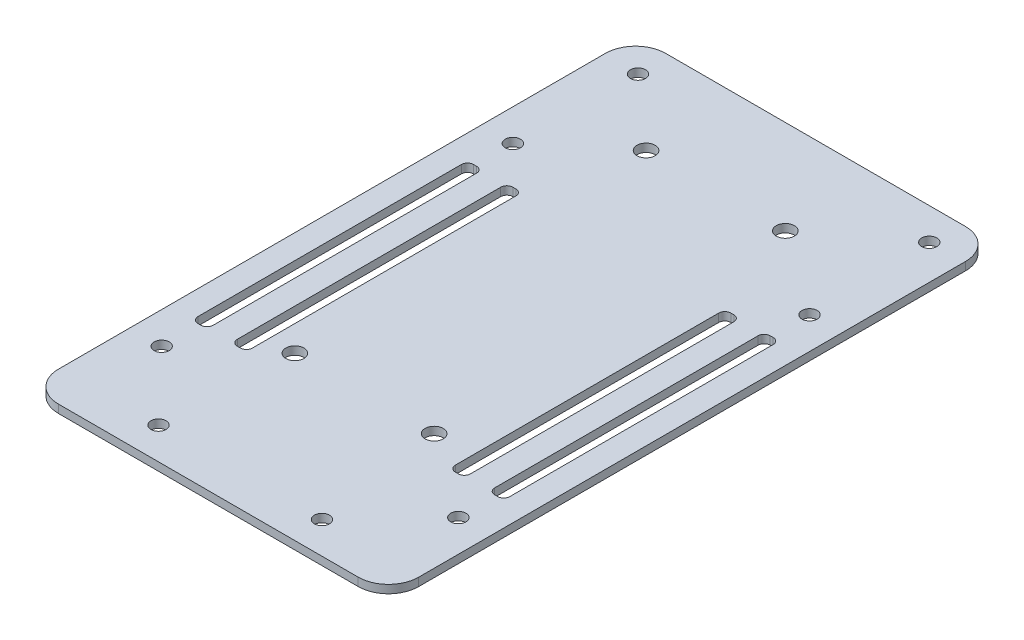
SolidWorks part; units mm, degrees
ref_plane "Front Plane" through (0, 0, 0) normal (0, 0, 1) x (1, 0, 0)
ref_plane "Top Plane" through (0, 0, 0) normal (0, 1, 0) x (1, 0, 0)
ref_plane "Right Plane" through (0, 0, 0) normal (1, 0, 0) x (0, 0, -1)
sketch "Sketch1" plane through (0, 0, 0) normal (0, 1, 0) x (1, 0, 0)
  line L0 (-14, 37.2419) -> (-14, -15.5619) construction
  line L1 (-14, 37.2419) -> (-14, -15.5619)
  line L2 (12, -15.5619) -> (12, 37.2419) construction
  line L3 (12, -15.5619) -> (12, 37.2419)
  line L4 (11, 43.34) -> (-13, 43.34)
  line L5 (-16, 40.34) -> (-16, -18.66)
  line L6 (-19.25, -26.0566) -> (-11.2385, -34.45)
  line L7 (-11.2385, -34.45) -> (11.2499, -34.45)
  line L8 (11.2499, -34.45) -> (19.25, -26.0457)
  line L9 (19.25, -26.0457) -> (19.25, 44.85)
  line L10 (19.25, 44.85) -> (-19.25, 44.85)
  line L11 (-19.25, 44.85) -> (-19.25, -26.0566)
  line L12 (-19.25, -26.0566) -> (-11.2385, -34.45)
  line L13 (-11.2385, -34.45) -> (11.2499, -34.45)
  line L14 (11.2499, -34.45) -> (19.25, -26.0457)
  line L15 (19.25, -26.0457) -> (19.25, 44.85)
  line L16 (19.25, 44.85) -> (-19.25, 44.85)
  line L17 (-19.25, 44.85) -> (-19.25, -26.0566)
  line L18 (-29.75, -30.2634) -> (-15.7315, -44.95)
  line L19 (-15.7315, -44.95) -> (15.7516, -44.95)
  line L20 (15.7516, -44.95) -> (29.75, -30.2443)
  line L21 (29.75, -30.2443) -> (29.75, 55.35)
  line L22 (29.75, 55.35) -> (-29.75, 55.35)
  line L23 (-29.75, 55.35) -> (-29.75, -30.2634)
  line L24 (-29.75, -30.2634) -> (-15.7315, -44.95)
  line L25 (-15.7315, -44.95) -> (15.7516, -44.95)
  line L26 (15.7516, -44.95) -> (29.75, -30.2443)
  line L27 (29.75, -30.2443) -> (29.75, 55.35)
  line L28 (29.75, 55.35) -> (-29.75, 55.35)
  line L29 (-29.75, 55.35) -> (-29.75, -30.2634)
  line L30 (-13, -21.66) -> (11, -21.66)
  line L31 (14, -18.66) -> (14, 40.34)
  line L32 (11, 43.34) -> (-13, 43.34)
  line L33 (-16, 40.34) -> (-16, -18.66)
  line L34 (-13, -21.66) -> (11, -21.66)
  line L35 (14, -18.66) -> (14, 40.34)
  line L36 (-9.9019, 41.34) -> (7.9019, 41.34) construction
  line L37 (-9.9019, 41.34) -> (7.9019, 41.34)
  line L38 (7.9029, -19.6617) -> (-9.9029, -19.6617) construction
  line L39 (7.9029, -19.6617) -> (-9.9029, -19.6617)
  circle A0 centre (10.5, -18.16) radius 1.5 construction
  circle A1 centre (-24.085, 50.1) radius 1.25
  circle A2 centre (-24.085, 50.1) radius 1.25
  circle A3 centre (-24.5, 29.84) radius 1.25
  circle A4 centre (-24.5, 29.84) radius 1.25
  circle A5 centre (-24.5, -28.16) radius 1.25
  circle A6 centre (-24.5, -28.16) radius 1.25
  circle A7 centre (-13.485, -39.7) radius 1.25
  circle A8 centre (-13.485, -39.7) radius 1.25
  circle A9 centre (13.515, -39.7) radius 1.25
  circle A10 centre (13.515, -39.7) radius 1.25
  circle A11 centre (24.5, -28.16) radius 1.25
  circle A12 centre (24.5, -28.16) radius 1.25
  circle A13 centre (24.015, 50.1) radius 1.25
  circle A14 centre (24.015, 50.1) radius 1.25
  circle A15 centre (24.5, 29.84) radius 1.25
  circle A16 centre (24.5, 29.84) radius 1.25
  circle A17 centre (24.5, -28.16) radius 1.25
  circle A18 centre (24.5, -28.16) radius 1.25
  circle A19 centre (-24.5, -28.16) radius 1.25
  circle A20 centre (-24.5, -28.16) radius 1.25
  circle A21 centre (24.5, 29.84) radius 1.25
  circle A22 centre (24.5, 29.84) radius 1.25
  circle A23 centre (-24.5, 29.84) radius 1.25
  circle A24 centre (-24.5, 29.84) radius 1.25
  circle A25 centre (24.015, 50.1) radius 1.35
  circle A26 centre (24.015, 50.1) radius 1.35
  circle A27 centre (-24.085, 50.1) radius 1.35
  circle A28 centre (-24.085, 50.1) radius 1.35
  circle A29 centre (13.515, -39.7) radius 1.35
  circle A30 centre (13.515, -39.7) radius 1.35
  circle A31 centre (-13.485, -39.7) radius 1.35
  circle A32 centre (-13.485, -39.7) radius 1.35
  circle A33 centre (-12.5, -18.16) radius 1.5 construction
  circle A34 centre (-12.5, 39.84) radius 1.5 construction
  circle A35 centre (10.5, 39.84) radius 1.5 construction
  arc A36 (14, 40.34) -> (11, 43.34) centre (11, 40.34) ccw
  arc A37 (-13, 43.34) -> (-16, 40.34) centre (-13, 40.34) ccw
  arc A38 (-16, -18.66) -> (-13, -21.66) centre (-13, -18.66) ccw
  arc A39 (11, -21.66) -> (14, -18.66) centre (11, -18.66) ccw
  arc A40 (14, 40.34) -> (11, 43.34) centre (11, 40.34) ccw
  arc A41 (-13, 43.34) -> (-16, 40.34) centre (-13, 40.34) ccw
  arc A42 (-16, -18.66) -> (-13, -21.66) centre (-13, -18.66) ccw
  arc A43 (11, -21.66) -> (14, -18.66) centre (11, -18.66) ccw
  circle A44 centre (10.5, -18.16) radius 1.5
  circle A45 centre (-12.5, -18.16) radius 1.5
  circle A46 centre (-12.5, 39.84) radius 1.5
  circle A47 centre (10.5, 39.84) radius 1.5
  arc A48 (-14, 37.2419) -> (-9.9019, 41.34) centre (-12.5, 39.84) ccw construction
  arc A49 (-14, 37.2419) -> (-9.9019, 41.34) centre (-12.5, 39.84) ccw
  arc A50 (7.9019, 41.34) -> (12, 37.2419) centre (10.5, 39.84) ccw construction
  arc A51 (7.9019, 41.34) -> (12, 37.2419) centre (10.5, 39.84) ccw
  spline S0 degree 3 poles (-1943.7151, 104.3141) (532.4017, -849.915) (655.7607, 1201.4441) (-1573.6161, -1182.5299) knots -35.201271 -35.201271 -35.201271 -35.201271 31.21294 31.21294 31.21294 31.21294 weights 1 1 1 1 only from (10.6435, 12.1281) to (8.2337, 17.8558) construction
  spline S1 degree 3 poles (10.6435, 12.1281) (10.3736, 14.2585) (9.5703, 16.1762) (8.2337, 17.8558) knots 0 0 0 0 1 1 1 1 weights 1 1 1 1
  dimension "D1" = 0
  dimension "D2" = 0
  dimension "D3" = 0
  dimension "D4" = 0
  dimension "D5" = 0
  dimension "D6" = 0
  dimension "D7" = 0
  dimension "D8" = 0
  dimension "D9" = 0
  dimension "D10" = 0
  dimension "D11" = 0
  dimension "D12" = 0
  dimension "D13" = 0
  dimension "D14" = 0
  dimension "D15" = 0
  dimension "D16" = 0
  dimension "D17" = 0
  dimension "D18" = 0
  dimension "D19" = 0
sketch "Sketch2" plane through (0, 0, 0) normal (0, 1, 0) x (1, 0, 0)
  line L0 (-29.75, 55.35) -> (-29.75, -30.2634) construction
  line L1 (29.75, -30.2443) -> (29.75, 55.35) construction
  line L2 (29.75, 55.35) -> (-29.75, 55.35) construction
  line L4 (-29.75, 55.35) -> (-29.75, -44.95)
  line L5 (29.75, -44.95) -> (29.75, 55.35)
  line L6 (29.75, 55.35) -> (-29.75, 55.35)
  line L7 (-29.75, -44.95) -> (29.75, -44.95)
  line L8 (-15.7315, -44.95) -> (15.7516, -44.95) construction
  circle A0 centre (-24.5, 29.84) radius 1.25 construction
  circle A1 centre (-24.085, 50.1) radius 1.25 construction
  circle A2 centre (24.015, 50.1) radius 1.25 construction
  circle A3 centre (24.5, 29.84) radius 1.25 construction
  circle A4 centre (24.5, -28.16) radius 1.25 construction
  circle A5 centre (-24.5, -28.16) radius 1.25 construction
  circle A6 centre (-13.485, -39.7) radius 1.25 construction
  circle A7 centre (13.515, -39.7) radius 1.25 construction
  circle A8 centre (-24.5, 29.84) radius 1.25
  circle A9 centre (-24.085, 50.1) radius 1.25
  circle A10 centre (24.015, 50.1) radius 1.25
  circle A11 centre (24.5, 29.84) radius 1.25
  circle A12 centre (24.5, -28.16) radius 1.25
  circle A13 centre (-24.5, -28.16) radius 1.25
  circle A14 centre (-13.485, -39.7) radius 1.25
  circle A15 centre (13.515, -39.7) radius 1.25
  circle A16 centre (-12.5, -18.16) radius 1.5 construction
  circle A17 centre (10.5, -18.16) radius 1.5 construction
  circle A18 centre (10.5, 39.84) radius 1.5 construction
  circle A19 centre (-12.5, 39.84) radius 1.5 construction
  circle A20 centre (-12.5, -18.16) radius 1.5
  circle A21 centre (10.5, -18.16) radius 1.5
  circle A22 centre (10.5, 39.84) radius 1.5
  circle A23 centre (-12.5, 39.84) radius 1.5
  point P42 (0, 0)
  point P43 (0, 0)
  point P44 (0, 0)
  point P45 (0, 0)
  point P46 (29.75, -56.9717)
extrude "Boss-Extrude1" add sketch "Sketch2" along normal blind 1.35
fillet "Fillet1" radius 5 4 edges at (-29.75, 0.675, -55.35) (29.75, 0.675, -55.35) (-29.75, 0.675, 44.95) (29.75, 0.675, 44.95)
sketch "Sketch3" plane through (0, 1.35, 0) normal (0, 1, 0) x (1, 0, 0)
  line L0 (-24.5, 29.84) -> (-24.5, -28.16) construction
  line L1 (0, 29.84) -> (0, -28.16) construction
  line L2 (-19.25, 44.85) -> (-19.25, -26.0566) construction
  line L3 (-19.25, 44.85) -> (-19.25, -26.0566) construction
  line L4 (-24.5, 0.84) -> (0, 0.84) construction
  line L5 (19.25, -21.91) -> (16.75, -21.91)
  line L6 (-25.75, 23.59) -> (-23.25, 23.59)
  line L7 (-25.75, 23.59) -> (-25.75, -21.91)
  line L8 (-25.75, -21.91) -> (-23.25, -21.91)
  line L9 (-23.25, 23.59) -> (-23.25, -21.91)
  line L10 (-25.75, 23.59) -> (-23.25, -21.91) construction
  line L11 (-25.75, -21.91) -> (-23.25, 23.59) construction
  line L12 (-19.25, 23.59) -> (-16.75, 23.59)
  line L13 (-19.25, 23.59) -> (-19.25, -21.91)
  line L14 (-19.25, -21.91) -> (-16.75, -21.91)
  line L15 (-16.75, 23.59) -> (-16.75, -21.91)
  line L16 (-19.25, 23.59) -> (-16.75, -21.91) construction
  line L17 (-19.25, -21.91) -> (-16.75, 23.59) construction
  line L18 (16.75, 23.59) -> (16.75, -21.91)
  line L19 (19.25, 23.59) -> (16.75, 23.59)
  line L20 (19.25, 23.59) -> (19.25, -21.91)
  line L21 (25.75, -21.91) -> (23.25, -21.91)
  line L22 (23.25, 23.59) -> (23.25, -21.91)
  line L23 (25.75, 23.59) -> (23.25, 23.59)
  line L24 (25.75, 23.59) -> (25.75, -21.91)
  circle A0 centre (-24.5, 29.84) radius 1.25 construction
  point P15 (-18, 0.84)
  point P22 (-24.5, 28.59)
  dimension "D1" = 5
extrude "Cut-Extrude1" cut sketch "Sketch3" against normal up to next
fillet "Fillet2" radius 1 16 edges at (23.25, 0.675, 21.91) (-19.25, 0.675, 21.91) (16.75, 0.675, 21.91) (-25.75, 0.675, 21.91) (-23.25, 0.675, 21.91) (-16.75, 0.675, 21.91) (19.25, 0.675, 21.91) (25.75, 0.675, 21.91) (19.25, 0.675, -23.59) (25.75, 0.675, -23.59) (-23.25, 0.675, -23.59) (-16.75, 0.675, -23.59) (23.25, 0.675, -23.59) (16.75, 0.675, -23.59) (-19.25, 0.675, -23.59) (-25.75, 0.675, -23.59)
equation "\"Black_acrylic\"= 1.35mm"
equation "\"MDF_base\"= 20mm"
equation "\"Supports_material\"= 5.4mm"
